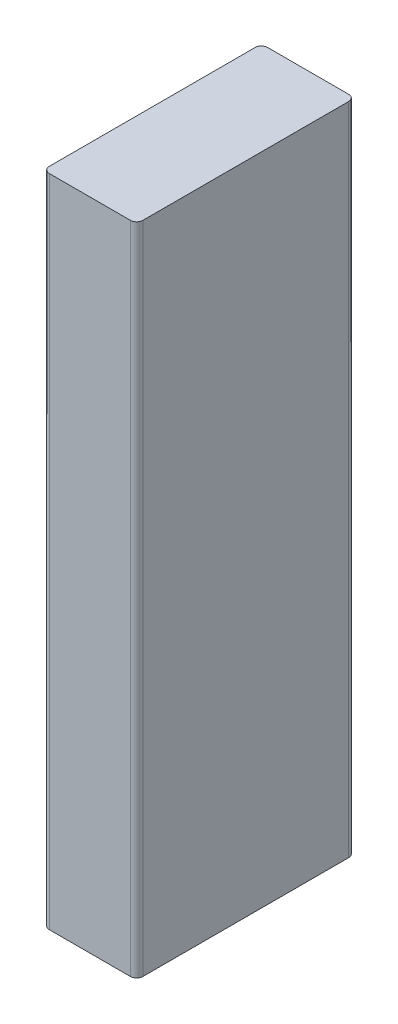
SolidWorks part; units mm, degrees
material "Pine"
ref_plane "Front Plane" through (0, 0, 0) normal (0, 0, 1) x (1, 0, 0)
ref_plane "Top Plane" through (0, 0, 0) normal (0, 1, 0) x (1, 0, 0)
ref_plane "Right Plane" through (0, 0, 0) normal (1, 0, 0) x (0, 0, -1)
sketch "Sketch1" plane through (0, 0, 0) normal (0, 1, 0) x (1, 0, 0)
  line L1 (-19.05, -44.45) -> (19.05, -44.45)
  line L2 (-19.05, -44.45) -> (-19.05, 44.45)
  line L3 (-19.05, 44.45) -> (19.05, 44.45)
  line L4 (19.05, -44.45) -> (19.05, 44.45)
  line L5 (-19.05, -44.45) -> (19.05, 44.45) construction
  line L6 (-19.05, 44.45) -> (19.05, -44.45) construction
  point P0 (0, 0)
  dimension "D1" = 88.9
  dimension "D2" = 38.1
extrude "Boss-Extrude1" add sketch "Sketch1" along normal blind 266.7
fillet "Fillet1" radius 2.54 4 edges at (-19.05, 133.35, -44.45) (19.05, 133.35, -44.45) (-19.05, 133.35, 44.45) (19.05, 133.35, 44.45)
